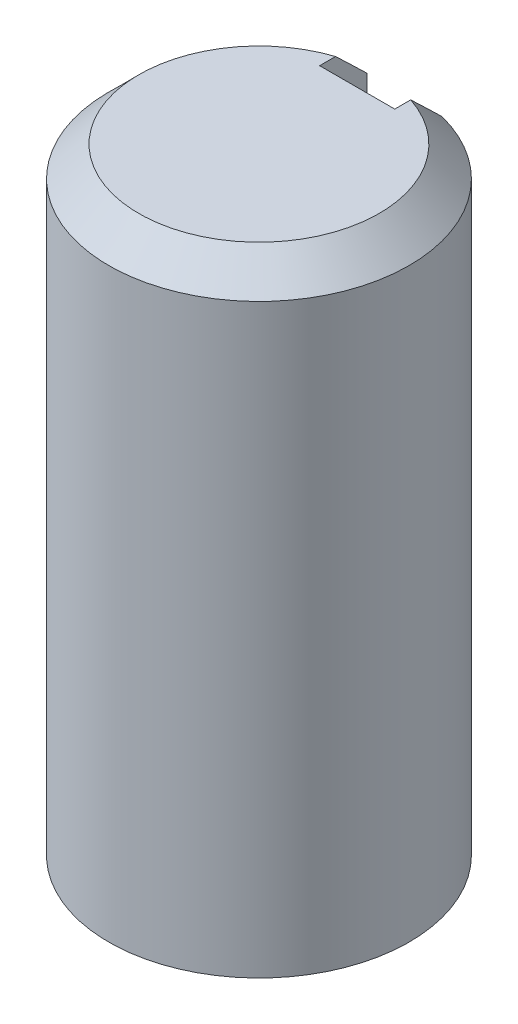
SolidWorks part; units mm, degrees
ref_plane "Спереди" through (0, 0, 0) normal (0, 0, 1) x (1, 0, 0)
ref_plane "Сверху" through (0, 0, 0) normal (0, 1, 0) x (1, 0, 0)
ref_plane "Справа" through (0, 0, 0) normal (1, 0, 0) x (0, 0, -1)
sketch "Эскиз1" plane through (0, 0, 0) normal (0, 1, 0) x (1, 0, 0)
  circle A0 centre (0, 0) radius 10
  dimension "D1" = 20
extrude "Бобышка-Вытянуть1" add sketch "Эскиз1" along normal blind 41
sketch "Эскиз2" plane through (0, 41, 0) normal (0, 1, 0) x (1, 0, 0)
  line L0 (0, 10) -> (0, -10) construction
  line L2 (-2.5, 10.4525) -> (2.5, 10.4525)
  line L3 (-2.5, 10.4525) -> (-2.5, 6.5383)
  line L4 (-2.5, 6.5383) -> (2.5, 6.5383)
  line L5 (2.5, 10.4525) -> (2.5, 6.5383)
  circle A0 centre (0, 0) radius 10 construction
  circle A1 centre (0, 0) radius 7 construction
  dimension "D1" = 14
  dimension "D2" = 5
  dimension "D3" = 2.5
extrude "Вырез-Вытянуть1" cut sketch "Эскиз2" against normal blind 48
sketch "Эскиз3" plane through (0, 41, 0) normal (0, 1, 0) x (1, 0, 0)
  circle A0 centre (0, 0) radius 7
  dimension "D1" = 14
extrude "Вырез-Вытянуть2" [suppressed] cut sketch "Эскиз3" against normal blind 37
chamfer "Фаска1" distance 2 angle 45 1 edges at (0, 41, 10)
